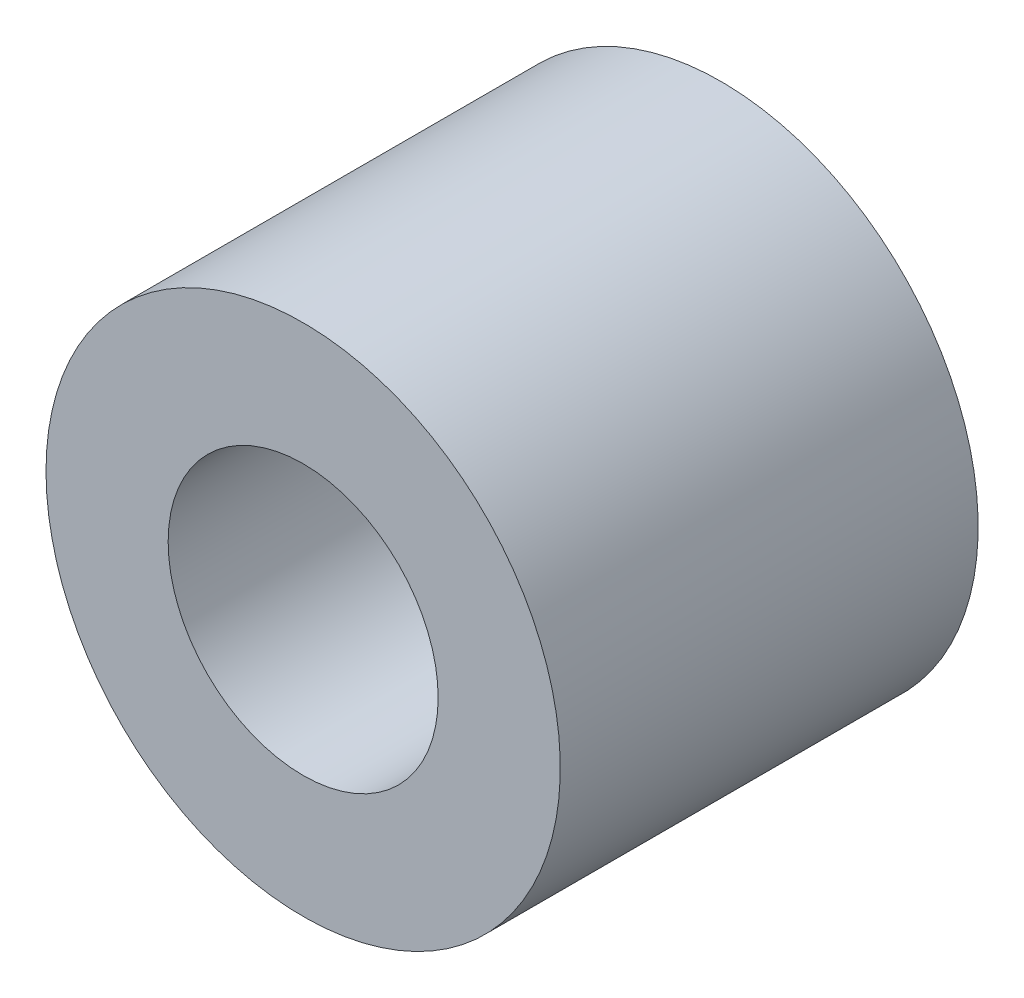
SolidWorks part; units mm, degrees
ref_plane "正面" through (0, 0, 0) normal (0, 0, 1) x (1, 0, 0)
ref_plane "平面" through (0, 0, 0) normal (0, 1, 0) x (1, 0, 0)
ref_plane "右側面" through (0, 0, 0) normal (1, 0, 0) x (0, 0, -1)
sketch "ｽｹｯﾁ1" plane through (0, 0, 0) normal (0, 0, 1) x (1, 0, 0)
  circle A0 centre (0, 0) radius 2.1
  circle A1 centre (0, 0) radius 4
  dimension "D1" = 4.2
  dimension "D2" = 8
extrude "ﾎﾞｽ - 押し出し1" add sketch "ｽｹｯﾁ1" along normal blind 6.5
